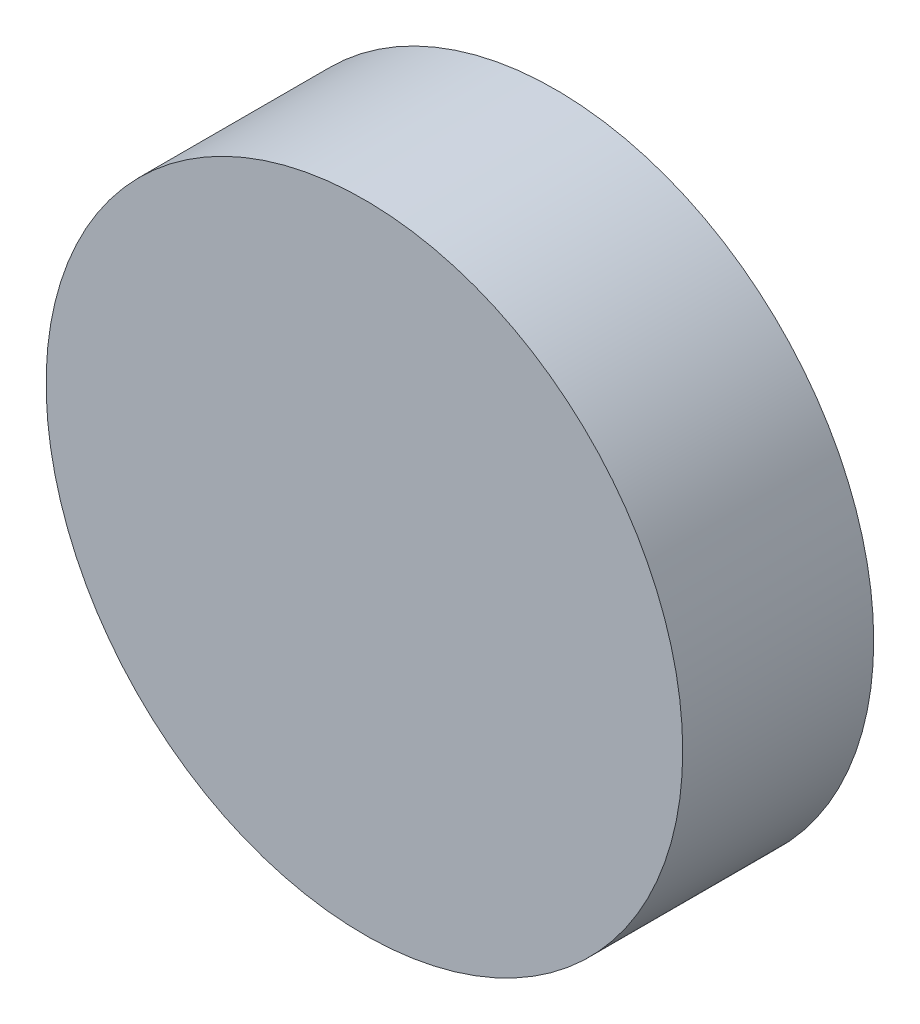
SolidWorks part; units mm, degrees
ref_plane "前视基准面" through (0, 0, 0) normal (0, 0, 1) x (1, 0, 0)
ref_plane "上视基准面" through (0, 0, 0) normal (0, 1, 0) x (1, 0, 0)
ref_plane "右视基准面" through (0, 0, 0) normal (1, 0, 0) x (0, 0, -1)
sketch "草图1" plane through (0, 0, 0) normal (0, 0, 1) x (1, 0, 0)
  circle A0 centre (0, 0) radius 5
extrude "凸台-拉伸1" add sketch "草图1" along normal blind 3
